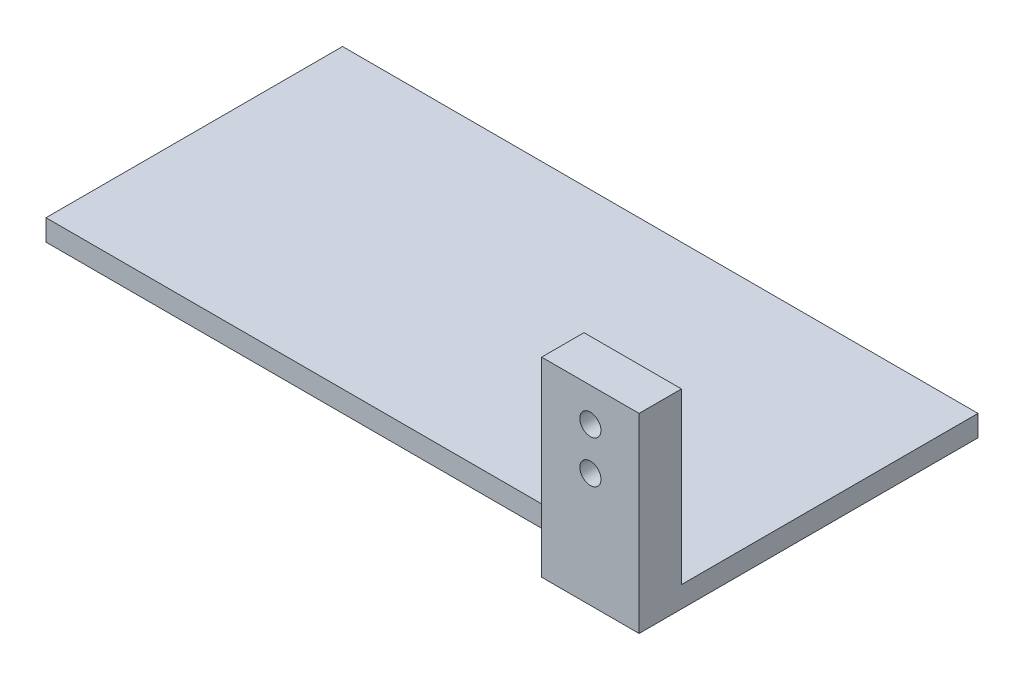
SolidWorks part; units mm, degrees
material "1060 Alloy"
ref_plane "Front Plane" through (0, 0, 0) normal (0, 0, 1) x (1, 0, 0)
ref_plane "Top Plane" through (0, 0, 0) normal (0, 1, 0) x (1, 0, 0)
ref_plane "Right Plane" through (0, 0, 0) normal (1, 0, 0) x (0, 0, -1)
sketch "Sketch2" plane through (0, 0, 0) normal (0, 1, 0) x (1, 0, 0)
  line L5 (-11.5, 5) -> (11.5, 5)
  line L6 (-11.5, 5) -> (-11.5, -5)
  line L7 (-11.5, -5) -> (11.5, -5)
  line L8 (11.5, 5) -> (11.5, -5)
  line L9 (-11.5, 5) -> (11.5, -5) construction
  line L10 (-11.5, -5) -> (11.5, 5) construction
  point P0 (0, 0)
  dimension "D1" = 23
  dimension "D2" = 10
extrude "Boss-Extrude1" add sketch "Sketch2" along normal blind 40
sketch "Sketch3" plane through (0, 0, 5) normal (0, 0, 1) x (1, 0, 0)
  line L0 (-11.5, 40) -> (11.5, 40) construction
  line L1 (-11.5, 40) -> (-11.5, 0) construction
  circle A0 centre (0, 32) radius 2.5
  circle A1 centre (0, 22) radius 2.5
  dimension "D1" = 5
  dimension "D2" = 5
  dimension "D3" = 8
  dimension "D4" = 10
  dimension "D5" = 11.5
extrude "Cut-Extrude1" cut sketch "Sketch3" against normal through all
sketch "Sketch4" plane through (0, 0, 5) normal (0, 0, 1) x (1, 0, 0)
  line L0 (11.5, 40) -> (11.5, 0) construction
  line L1 (-138.5, 0) -> (11.5, 0)
  line L2 (-138.5, 0) -> (-138.5, -5)
  line L3 (-138.5, -5) -> (11.5, -5)
  line L4 (11.5, 0) -> (11.5, -5)
  line L5 (-138.5, 0) -> (11.5, -5) construction
  line L6 (-138.5, -5) -> (11.5, 0) construction
  line L7 (-11.5, 0) -> (11.5, 0) construction
  point P0 (-63.5, -2.5)
  dimension "D1" = 150
  dimension "D2" = 5
extrude "Boss-Extrude2" add sketch "Sketch4" against normal blind 70 from offset 10 offset against normal yes
sketch "Sketch5" plane through (0, 0, 0) normal (0, -1, 0) x (1, 0, 0)
  line L4 (11.5, -5) -> (11.5, 5)
  line L5 (11.5, 5) -> (-11.5, 5)
  line L6 (-11.5, 5) -> (-11.5, -5)
  line L7 (-11.5, -5) -> (11.5, -5)
  line L8 (11.5, -5) -> (11.5, 5)
  line L9 (11.5, 5) -> (-11.5, 5)
  line L10 (-11.5, 5) -> (-11.5, -5)
  line L11 (-11.5, -5) -> (11.5, -5)
  dimension "D1" = 0
extrude "Boss-Extrude3" add sketch "Sketch5" along normal blind 5
